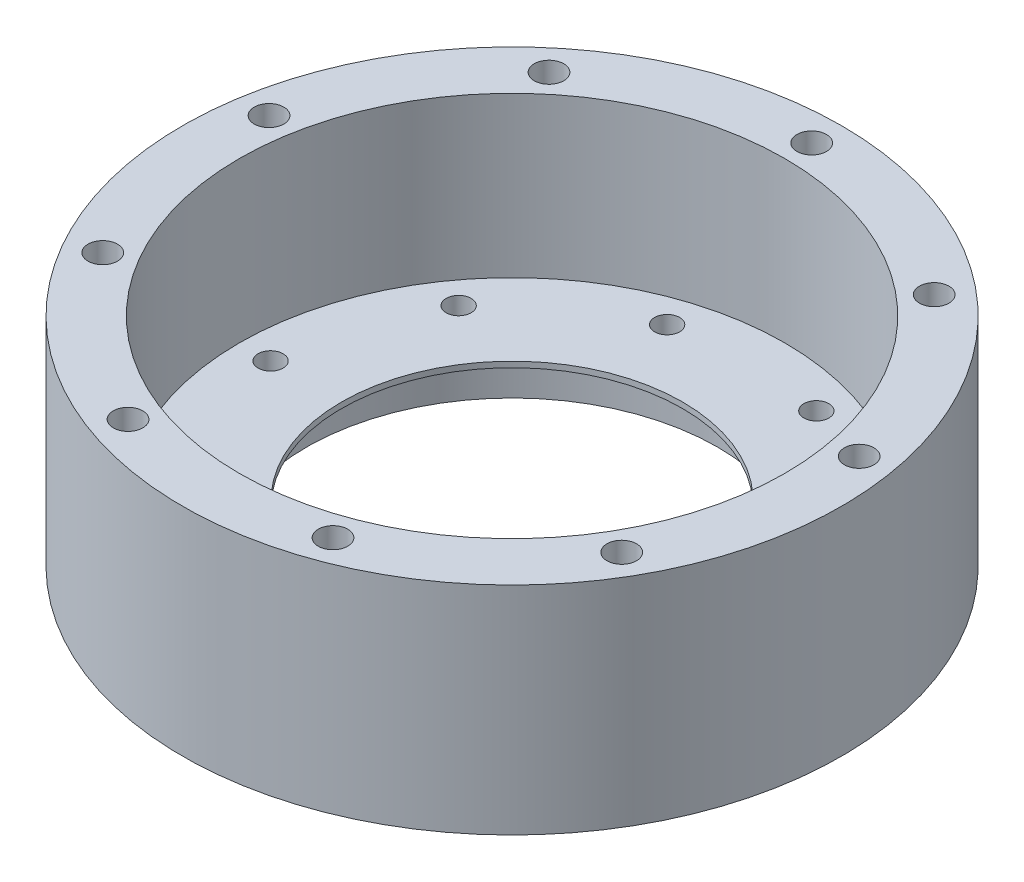
SolidWorks part; units mm, degrees
other "Markup1"
sketch "Sketch11" plane through (58, 0, 58) normal (0.706, -0.3119, 0.6358) x (0.477, 0.8731, -0.1013)
other "Markup2"
sketch "Sketch12" plane through (58, 38.1, 58) normal (0.2322, 0.8653, 0.4441) x (0.5509, 0.2593, -0.7933)
other "Markup3"
sketch "Sketch14" plane through (58, 38.1, -58) normal (0.7809, 0.5998, -0.1747) x (-0.3182, 0.1412, -0.9374)
other "Markup4"
sketch "Sketch17" plane through (58, 38.1, -58) normal (0.3812, 0.5861, -0.7149) x (-0.9, 0.0585, -0.4319)
other "Markup5"
sketch "Sketch18" plane through (58, 38.1, -58) normal (0.3812, 0.5861, -0.7149) x (-0.9, 0.0585, -0.4319)
ref_plane "Front Plane" through (0, 0, 0) normal (0, 0, 1) x (1, 0, 0)
ref_plane "Top Plane" through (0, 0, 0) normal (0, 1, 0) x (1, 0, 0)
ref_plane "Right Plane" through (0, 0, 0) normal (1, 0, 0) x (0, 0, -1)
sketch "Sketch1" plane through (0, 0, 0) normal (0, 1, 0) x (1, 0, 0)
  circle A0 centre (0, 0) radius 58
  dimension "D1" = 116
extrude "Boss-Extrude1" add sketch "Sketch1" along normal blind 38.1
sketch "Sketch2" plane through (0, 38.1, 0) normal (0, 1, 0) x (1, 0, 0)
  circle A0 centre (0, 0) radius 48
  dimension "D1" = 96
extrude "Cut-Extrude1" cut sketch "Sketch2" against normal offset from surface (28.1 mm away) 10 up to face at (0, 0, 58)
sketch "OuterPin Dimensions" plane through (0, 10, 0) normal (0, 1, 0) x (1, 0, 0)
  circle A0 centre (0, 0) radius 38.5 construction
  circle A1 centre (13.1332, 40.4199) radius 4
  dimension "D1" = 77
  dimension "D2" = 8
  dimension "D3" = 13.1332
sketch "Sketch5" plane through (0, 38.1, 0) normal (0, 1, 0) x (1, 0, 0)
  circle A0 centre (0, 52.7318) radius 2.6
  circle A1 centre (33.8954, 40.3949) radius 2.6
  circle A2 centre (51.9307, 9.1568) radius 2.6
  circle A3 centre (45.6671, -26.3659) radius 2.6
  circle A4 centre (18.0354, -49.5517) radius 2.6
  circle A5 centre (-18.0354, -49.5517) radius 2.6
  circle A6 centre (-45.6671, -26.3659) radius 2.6
  circle A7 centre (-51.9307, 9.1568) radius 2.6
  circle A8 centre (-33.8954, 40.3949) radius 2.6
  point P20 (0, 0)
  dimension "D1" = 5.2
  dimension "D2" = 9
sketch "Sketch6" plane through (0, 0, 0) normal (0, -1, 0) x (1, 0, 0)
  circle A0 centre (13.1332, -40.4199) radius 4 construction
  circle A1 centre (13.1332, -40.4199) radius 4 construction
  circle A2 centre (13.1332, -40.4199) radius 2.2
  circle A3 centre (-13.1332, -40.4199) radius 2.2
  circle A4 centre (-34.3832, -24.9809) radius 2.2
  circle A5 centre (-42.5, 0) radius 2.2
  circle A6 centre (-34.3832, 24.9809) radius 2.2
  circle A7 centre (-13.1332, 40.4199) radius 2.2
  circle A8 centre (13.1332, 40.4199) radius 2.2
  circle A9 centre (34.3832, 24.9809) radius 2.2
  circle A10 centre (42.5, 0) radius 2.2
  circle A11 centre (34.3832, -24.9809) radius 2.2
  point P25 (0, 0)
  dimension "D1" = 4.4
  dimension "D3" = 4.4
  dimension "D2" = 10
extrude "Fastening Holes" cut sketch "Sketch5" against normal through all
sketch "Sketch9" plane through (0, 0, 0) normal (0, -1, 0) x (1, 0, 0)
  circle A0 centre (0, 0) radius 36.2
  dimension "D1" = 72.4
extrude "Cut-Extrude2" cut sketch "Sketch9" against normal blind 9
sketch "Sketch10" plane through (0, 9, 0) normal (0, -1, 0) x (1, 0, 0)
  circle A0 centre (0, 0) radius 30
  dimension "D1" = 60
extrude "Cut-Extrude3" cut sketch "Sketch10" against normal through all
extrude "Cut-Extrude4" cut sketch "Sketch6" against normal through all
sketch "Sketch16" plane through (0, 0, 0) normal (0, -1, 0) x (1, 0, 0)
  circle A0 centre (-13.1332, 40.4199) radius 2.2 construction
  circle A1 centre (-13.1332, 40.4199) radius 2.2 construction
  circle A2 centre (-13.1332, 40.4199) radius 3.7
  circle A3 centre (13.1332, 40.4199) radius 3.7
  circle A4 centre (34.3832, 24.9809) radius 3.7
  circle A5 centre (42.5, 0) radius 3.7
  circle A6 centre (34.3832, -24.9809) radius 3.7
  circle A7 centre (13.1332, -40.4199) radius 3.7
  circle A8 centre (-13.1332, -40.4199) radius 3.7
  circle A9 centre (-34.3832, -24.9809) radius 3.7
  circle A10 centre (-42.5, 0) radius 3.7
  circle A11 centre (-34.3832, 24.9809) radius 3.7
  point P25 (0, 0)
  dimension "D1" = 7.4
  dimension "D2" = 10
extrude "Cut-Extrude5" cut sketch "Sketch16" against normal blind 2.2
